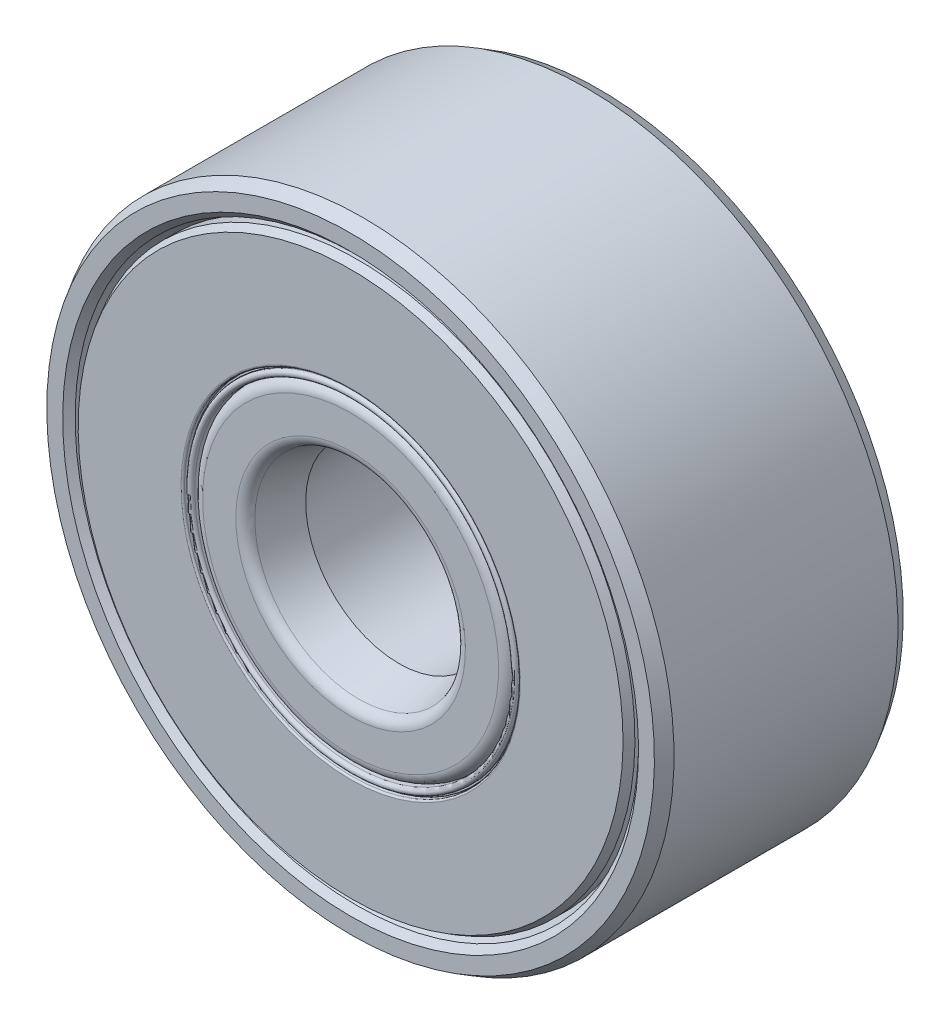
SolidWorks part; units mm, degrees
ref_plane "Front Plane" through (0, 0, 0) normal (0, 0, 1) x (1, 0, 0)
ref_plane "Top Plane" through (0, 0, 0) normal (0, 1, 0) x (1, 0, 0)
ref_plane "Right Plane" through (0, 0, 0) normal (1, 0, 0) x (0, 0, -1)
sketch "Sketch1" plane through (0, 0, 0) normal (0, 0, 1) x (1, 0, 0)
  line L0 (-5, 0) -> (5, 0) construction
  line L1 (-1.5, 0) -> (1.5, 0) construction
  circle A0 centre (0, 0) radius 1.5 construction
  circle A1 centre (0, 0) radius 5 construction
  point P3 (0, 0)
  point P6 (0, 0)
  point P7 (0, -1.5)
  point P11 (0, -5)
  point P12 (0, 1.5)
  point P13 (0, 5)
  dimension "OD" = 10
  dimension "ID" = 3
sketch "Sketch2" plane through (0, 0, 0) normal (1, 0, 0) x (0, 0, -1)
  line L0 (-2, 5) -> (2, 5) construction
  line L1 (0, 5) -> (0, -5) construction
  line L2 (1.8, 5) -> (-1.8, 5)
  line L3 (-1.8, 5) -> (-2, 4.8845)
  line L4 (-2, 4.8845) -> (-2, 4.629)
  line L5 (-1.683, 4.45) -> (-0.91, 4.45)
  line L6 (1.683, 4.45) -> (0.91, 4.45)
  line L7 (2, 4.8845) -> (2, 4.629)
  line L8 (1.8, 5) -> (2, 4.8845)
  line L9 (-0.91, 4.45) -> (-0.91, 4.6333) construction
  line L10 (-0.91, 4.6333) -> (-0.91, 4.8167) construction
  line L11 (0, 5) -> (0, -5) construction
  line L12 (-2, 0) -> (2, 0) construction
  line L13 (2, 1.5) -> (-2, 1.5) construction
  line L14 (-2, 1.5) -> (-2, -1.5) construction
  line L15 (-2, -1.5) -> (2, -1.5) construction
  line L16 (2, 5) -> (2, -5) construction
  line L17 (-0.91, 4.8167) -> (-0.91, 5) construction
  line L18 (-0.91, 4.8167) -> (0, 4.8167) construction
  line L20 (-1.683, 4.45) -> (-1.9, 4.529)
  line L21 (-1.9, 4.529) -> (-2, 4.629)
  line L26 (1.9, 4.529) -> (2, 4.629)
  line L27 (1.683, 4.45) -> (1.9, 4.529)
  arc A0 (-0.91, 4.45) -> (0.91, 4.45) centre (0, 3.5042) cw
  circle A1 centre (0, 3.5042) radius 1.3125 construction
  point P17 (0, 0)
  point P21 (0, 5)
  point P30 (0, -1.5)
  dimension "Approx. Ball Dia." = 2.625
  dimension "Width" = 4
  dimension "For Shaft Diameter" = 3
  dimension "For Housing ID" = 10
  dimension "D4" = 8.9
  dimension "D2" = 20
  dimension "D5" = 45
  dimension "D1" = 30
  dimension "D6" = 0.2
  dimension "D7" = 0.1
sketch "Sketch3" plane through (0, 0, 0) normal (1, 0, 0) x (0, 0, -1)
  line L14 (-1.683, 4.45) -> (-1.9, 4.529) construction
  line L15 (-1.9, 4.529) -> (-2, 4.629) construction
  line L16 (-2, 4.8845) -> (-2, 4.629) construction
  line L17 (-1.8, 5) -> (-2, 4.8845) construction
  line L18 (1.8, 5) -> (-1.8, 5) construction
  line L19 (1.8, 5) -> (2, 4.8845) construction
  line L20 (2, 4.8845) -> (2, 4.629) construction
  line L21 (1.9, 4.529) -> (2, 4.629) construction
  line L22 (1.683, 4.45) -> (1.9, 4.529) construction
  line L23 (1.683, 4.45) -> (0.91, 4.45) construction
  line L24 (-1.683, 4.45) -> (-0.91, 4.45) construction
  line L25 (-1.683, 4.45) -> (-1.9, 4.529)
  line L26 (-1.9, 4.529) -> (-2, 4.629)
  line L27 (-2, 4.8845) -> (-2, 4.629)
  line L28 (-1.8, 5) -> (-2, 4.8845)
  line L29 (1.8, 5) -> (-1.8, 5)
  line L30 (1.8, 5) -> (2, 4.8845)
  line L31 (2, 4.8845) -> (2, 4.629)
  line L32 (1.9, 4.529) -> (2, 4.629)
  line L33 (1.683, 4.45) -> (1.9, 4.529)
  line L34 (1.683, 4.45) -> (0.91, 4.45)
  line L35 (-1.683, 4.45) -> (-0.91, 4.45)
  arc A2 (0.91, 4.45) -> (-0.91, 4.45) centre (0, 3.5042) ccw construction
  arc A3 (0.91, 4.45) -> (-0.91, 4.45) centre (0, 3.5042) ccw
revolve "Revolve1" add sketch "Sketch3" angle 360 about L12
sketch "Sketch4" plane through (0, 0, 0) normal (1, 0, 0) x (0, 0, -1)
  line L0 (0, 5) -> (0, -5) construction
  line L1 (0, 5) -> (0, -5) construction
  line L2 (-1.222, 1.5) -> (-1.8673, 1.6729)
  line L3 (-2, 1.8458) -> (-2, 2.3793)
  line L4 (2, -4.8845) -> (2, 4.8845) construction
  line L5 (-1.821, 2.5583) -> (-0.91, 2.5583)
  line L6 (-1.222, 1.5) -> (1.222, 1.5)
  line L7 (2, 4.8845) -> (2, 4.629) construction
  line L8 (1.222, 1.5) -> (1.8673, 1.6729)
  line L9 (0, 4.8167) -> (0, 1.5) construction
  line L10 (2, 1.8458) -> (2, 2.3793)
  line L11 (1.821, 2.5583) -> (0.91, 2.5583)
  line L12 (1.222, 1.5) -> (1.222, 1.6729) construction
  line L13 (1.222, 1.6729) -> (1.222, 1.8458) construction
  line L14 (1.222, 1.8458) -> (1.222, 2.0187) construction
  line L15 (1.222, 2.0187) -> (1.222, 2.1917) construction
  circle A0 centre (0, 3.5042) radius 1.3125 construction
  arc A1 (0.91, 2.5583) -> (-0.91, 2.5583) centre (0, 3.5042) cw
  arc A2 (2, 2.3793) -> (1.821, 2.5583) centre (1.821, 2.3793) ccw
  arc A3 (-2, 2.3793) -> (-1.821, 2.5583) centre (-1.821, 2.3793) cw
  arc A4 (1.8673, 1.6729) -> (2, 1.8458) centre (1.821, 1.8458) ccw
  arc A5 (-1.8673, 1.6729) -> (-2, 1.8458) centre (-1.821, 1.8458) cw
  point P14 (2, 1.7085)
  point P36 (0, 2.1917)
  dimension "D1" = 15
revolve "Revolve2" add sketch "Sketch4" angle 360 about L12
sketch "Sketch5" plane through (0, 0, 0) normal (1, 0, 0) x (0, 0, -1)
  line L0 (-1.3125, 3.5042) -> (1.3125, 3.5042)
  arc A2 (-1.3125, 3.5042) -> (1.3125, 3.5042) centre (0, 3.5042) cw
  arc A3 (0.91, 4.45) -> (-0.91, 4.45) centre (0, 3.5042) ccw construction
revolve "Revolve3" add sketch "Sketch5" angle 360 about L0
pattern_circular "CirPattern1" count 7 over 360 about axis through (0, 0, 0) along (0, 0, 1) of bodies 104
sketch "Sketch6" plane through (0, 0, 0) normal (1, 0, 0) x (0, 0, -1)
  line L1 (-1.8788, 4.45) -> (-1.3125, 4.45)
  line L2 (-2, 4.38) -> (-2, 2.7263)
  line L3 (-1.972, 2.6983) -> (-1.3125, 2.6983)
  line L4 (-1.3125, 4.45) -> (-1.3125, 2.6983)
  line L5 (-2, 1.8458) -> (-2, 2.3793) construction
  line L6 (-1.8, 5) -> (-2, 4.8845) construction
  line L7 (0, 5) -> (0, 1.5) construction
  line L8 (1.972, 2.6983) -> (1.3125, 2.6983)
  line L9 (1.3125, 4.45) -> (1.3125, 2.6983)
  line L10 (1.8788, 4.45) -> (1.3125, 4.45)
  line L11 (2, 4.38) -> (2, 2.7263)
  line L13 (-1.821, 2.5583) -> (-0.91, 2.5583) construction
  line L14 (-2, 4.38) -> (-1.8788, 4.45)
  line L15 (-1.683, 4.45) -> (-0.91, 4.45) construction
  line L16 (2, 4.38) -> (1.8788, 4.45)
  arc A0 (-2, 2.7263) -> (-1.972, 2.6983) centre (-1.972, 2.7263) ccw
  circle A1 centre (0, 3.5042) radius 1.3125 construction
  arc A2 (2, 2.7263) -> (1.972, 2.6983) centre (1.972, 2.7263) cw
  point P26 (-2, 2.6983)
  dimension "D3" = 0.028
  dimension "D1" = 0.14
  dimension "D2" = 0.07
revolve "Revolve4" add sketch "Sketch6" angle 360 about L12
sketch "Sketch7" plane through (0, 0, 0) normal (1, 0, 0) x (0, 0, -1)
  line L3 (-1.3125, 2.6983) -> (-1.8906, 2.6983)
  line L4 (-1.972, 2.6983) -> (-1.3125, 2.6983) construction
  line L7 (0, 2.1917) -> (0, 1.5) construction
  line L8 (0, 5) -> (0, -5) construction
  line L21 (-1.8906, 2.6983) -> (-1.925, 2.6923)
  line L22 (-1.9225, 2.6633) -> (-1.9475, 2.6633)
  line L23 (-1.9475, 2.5583) -> (-1.3125, 2.5583)
  line L24 (-1.3125, 2.5583) -> (-1.3125, 2.6983)
  line L25 (-1.821, 2.5583) -> (-0.91, 2.5583) construction
  line L26 (-2, 2.7263) -> (-2, 2.5583) construction
  line L27 (-2, 2.5583) -> (-1.9475, 2.5583) construction
  line L28 (-1.8906, 2.6983) -> (-1.8906, 2.6633) construction
  line L29 (-1.8906, 2.6633) -> (-1.8906, 2.6283) construction
  line L30 (-1.8906, 2.6283) -> (-1.8906, 2.5933) construction
  line L31 (-1.8906, 2.5933) -> (-1.8906, 2.5583) construction
  circle A2 centre (0, 3.5042) radius 1.3125 construction
  arc A9 (-1.925, 2.6923) -> (-1.9225, 2.6633) centre (-1.9225, 2.6779) ccw
  arc A10 (-1.9475, 2.6633) -> (-1.9475, 2.5583) centre (-1.9475, 2.6108) ccw
  dimension "D1" = 0.025
  dimension "D2" = 10
revolve "Revolve5" add sketch "Sketch7" angle 360 about L12
equation "\"D4@Sketch2\"=\"OD@Sketch1\"*.89"
equation "\"D1@Sketch6\"=(\"OD@Sketch1\"-\"ID@Sketch1\")*.02"
equation "\"D2@Sketch6\"=\"D1@Sketch6\"*.5"
equation "\"D3@Sketch6\"=\"D1@Sketch6\"*.2"
equation "\"D6@Sketch2\"=\"Width@Sketch2\"*.05"
equation "\"D7@Sketch2\"=\"D6@Sketch2\"*.5"
equation "\"D1@CirPattern1\" =  ( pi * \"OD@Sketch1\" )  * .5625 / \"Approx. Ball Dia.@Sketch2\""
equation "\"Approx. Ball Dia.@Sketch2\"=(\"OD@Sketch1\"-\"ID@Sketch1\")*.5*.75"
